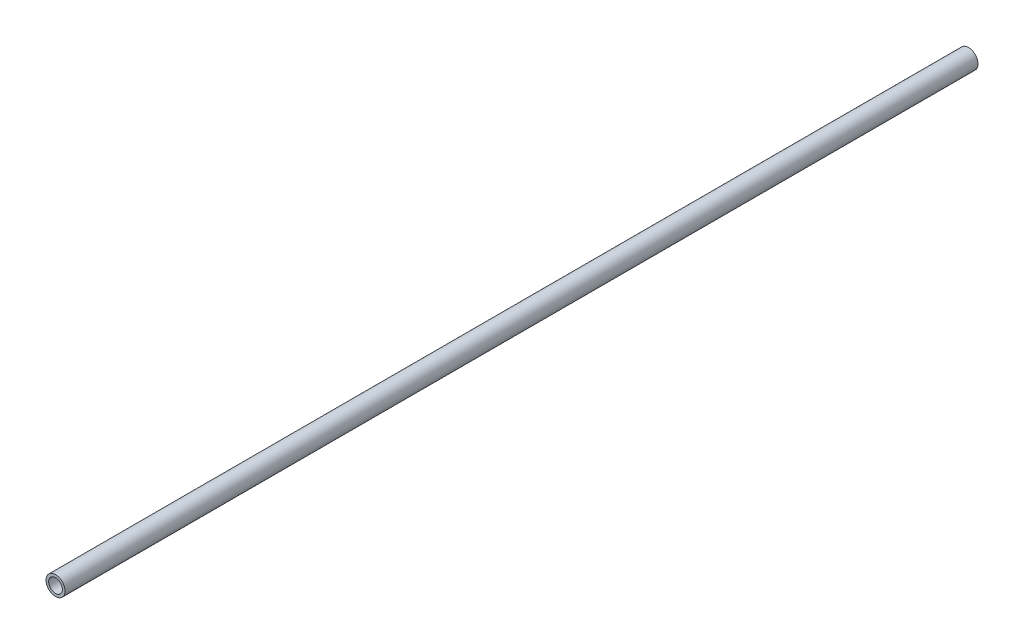
SolidWorks part; units mm, degrees
ref_plane "Front Plane" through (0, 0, 0) normal (0, 0, 1) x (1, 0, 0)
ref_plane "Top Plane" through (0, 0, 0) normal (0, 1, 0) x (1, 0, 0)
ref_plane "Right Plane" through (0, 0, 0) normal (1, 0, 0) x (0, 0, -1)
sketch "Sketch1" plane through (0, 0, 0) normal (0, 0, 1) x (1, 0, 0)
  line L0 (-3.175, 0) -> (3.175, 0) construction
  line L1 (0, -3.175) -> (0, 3.175) construction
  circle A0 centre (0, 0) radius 3.175
  circle A1 centre (0, 0) radius 2.286
  point P4 (0, 0)
  point P9 (0, 0)
  point P10 (2.286, 0)
  dimension "D1" = 4.572
  dimension "OD" = 6.35
  dimension "Wall Thickness" = 0.889
sketch "Sketch2" plane through (0, 0, 0) normal (1, 0, 0) x (0, 0, -1)
  line L0 (152.4, 3.175) -> (-152.4, 3.175) construction
  line L1 (0, 3.175) -> (0, -3.175) construction
  point P3 (-145.0975, 3.175)
  point P4 (0, 3.175)
  point P5 (145.0975, 3.175)
  dimension "D1" = 7.3025
  dimension "D2" = 7.3025
  dimension "Length" = 304.8
sketch "Sketch3" plane through (0, 0, 0) normal (0, 0, 1) x (1, 0, 0)
  line L0 (0, -3.175) -> (0, 3.175) construction
  circle A0 centre (0, 0) radius 3.175
  circle A1 centre (0, 0) radius 2.286
  circle A2 centre (0, 0) radius 2.286 construction
extrude "Boss-Extrude1" add sketch "Sketch3" along normal mid plane 304.8
equation "\"D1@Boss-Extrude1\" = \"Length@Sketch2\""
equation "\"D1@Sketch2\"=\"OD@Sketch1\"*1.15"
equation "\"D2@Sketch2\"=\"D1@Sketch2\""
